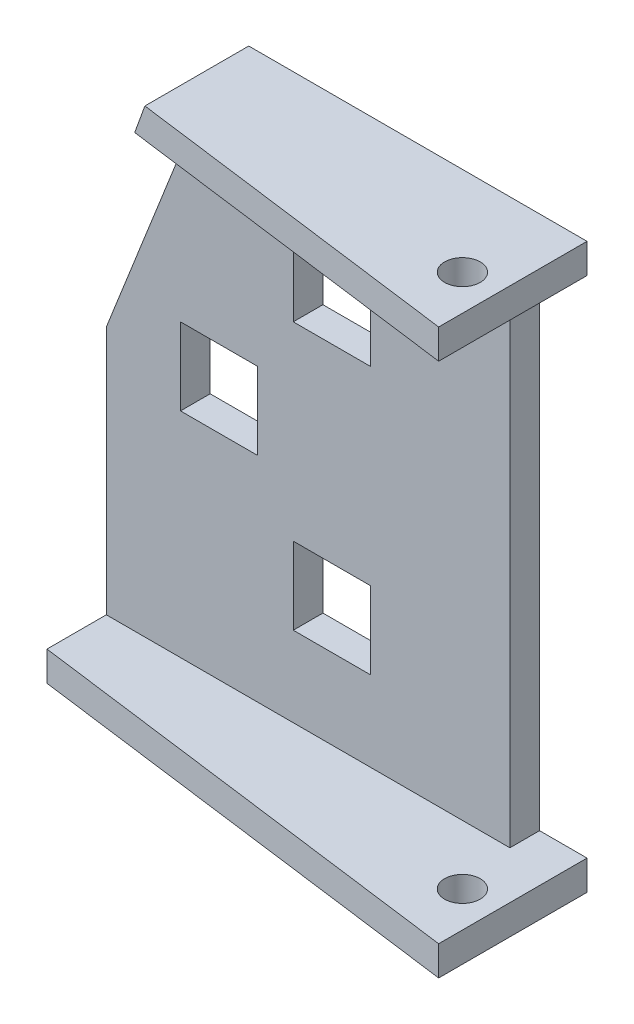
SolidWorks part; units mm, degrees
ref_plane "Front Plane" through (0, 0, 0) normal (0, 0, 1) x (1, 0, 0)
ref_plane "Top Plane" through (0, 0, 0) normal (0, 1, 0) x (1, 0, 0)
ref_plane "Right Plane" through (0, 0, 0) normal (1, 0, 0) x (0, 0, -1)
sketch "Sketch1" plane through (0, 0, 0) normal (0, 0, 1) x (1, 0, 0)
  line L0 (-70, 0) -> (6, 0)
  line L1 (6, 0) -> (6, 95)
  line L2 (6, 95) -> (-51, 95)
  line L3 (-51, 95) -> (-70, 47)
  line L4 (-70, 47) -> (-70, 0)
  dimension "D1" = 76
  dimension "D2" = 70
  dimension "D3" = 57
  dimension "D4" = 48
  dimension "D5" = 95
extrude "Boss-Extrude1" add sketch "Sketch1" along normal blind 5
sketch "Sketch2" plane through (0, 0, 5) normal (0, 0, 1) x (1, 0, 0)
  line L0 (6, 95) -> (-51, 95) construction
  line L1 (-38.5, 76.5) -> (-25.5, 76.5)
  line L2 (-38.5, 76.5) -> (-38.5, 63.5)
  line L3 (-38.5, 63.5) -> (-25.5, 63.5)
  line L4 (-25.5, 76.5) -> (-25.5, 63.5)
  line L5 (-38.5, 31.5) -> (-25.5, 31.5)
  line L6 (-38.5, 31.5) -> (-38.5, 18.5)
  line L7 (-38.5, 18.5) -> (-25.5, 18.5)
  line L8 (-25.5, 31.5) -> (-25.5, 18.5)
  line L9 (-57.5, 54) -> (-44.5, 54)
  line L10 (-57.5, 54) -> (-57.5, 41)
  line L11 (-57.5, 41) -> (-44.5, 41)
  line L12 (-44.5, 54) -> (-44.5, 41)
  line L13 (-70, 47) -> (-70, 0) construction
  point P12 (-25.5, 70)
  point P15 (-25.5, 25)
  point P16 (-44.5, 47.5)
  point P19 (-51, 41)
  point P20 (-32, 18.5)
  dimension "D1" = 25
  dimension "D2" = 70
  dimension "D3" = 47.5
  dimension "D4" = 19
  dimension "D5" = 38
  dimension "D6" = 13
extrude "Cut-Extrude1" cut sketch "Sketch2" against normal through all
sketch "Sketch5" plane through (0, 0, 5) normal (0, 0, 1) x (1, 0, 0)
  line L0 (-51, 95) -> (-52.9792, 90)
  line L1 (-51, 95) -> (-70, 47) construction
  line L2 (-52.9792, 90) -> (6, 90)
  line L3 (6, 0) -> (6, 95) construction
  line L4 (6, 90) -> (6, 95)
  line L5 (6, 95) -> (-51, 95)
  line L6 (-70, 0) -> (6, 0)
  line L7 (6, 0) -> (6, 5)
  line L8 (6, 5) -> (-70, 5)
  line L9 (-70, 47) -> (-70, 0) construction
  line L10 (-70, 5) -> (-70, 0)
  dimension "D1" = 5
  dimension "D2" = 5
extrude "Boss-Extrude3" add sketch "Sketch5" along normal blind 20
sketch "Sketch6" plane through (0, 0, 0) normal (0, -1, 0) x (1, 0, 0)
  line L1 (6, 25) -> (-70, 15)
  line L2 (-70, 25) -> (-70, 0) construction
  line L5 (-70, 15) -> (-70, 25)
  line L6 (-70, 25) -> (6, 25)
  line L7 (-70, 0) -> (6, 0) construction
  dimension "D1" = 15
extrude "Cut-Extrude2" cut sketch "Sketch6" against normal through all
sketch "Sketch7" plane through (0, 95, 0) normal (0, 1, 0) x (1, 0, 0)
  line L6 (6, -5) -> (-70, -5) construction
  line L7 (6, -25) -> (6, -5) construction
  circle A0 centre (0, -15) radius 3
  dimension "D1" = 6
  dimension "D2" = 10
  dimension "D3" = 6
extrude "Cut-Extrude4" cut sketch "Sketch7" against normal through all
sketch "Sketch8" plane through (0, 0, 5) normal (0, 0, 1) x (1, 0, 0)
  line L0 (-70, 5) -> (6, 5) construction
  line L1 (6, 90) -> (-2, 90)
  line L2 (6, 90) -> (6, 5)
  line L3 (6, 5) -> (-2, 5)
  line L4 (-2, 90) -> (-2, 5)
  dimension "D1" = 8
extrude "Cut-Extrude5" cut sketch "Sketch8" against normal through all
